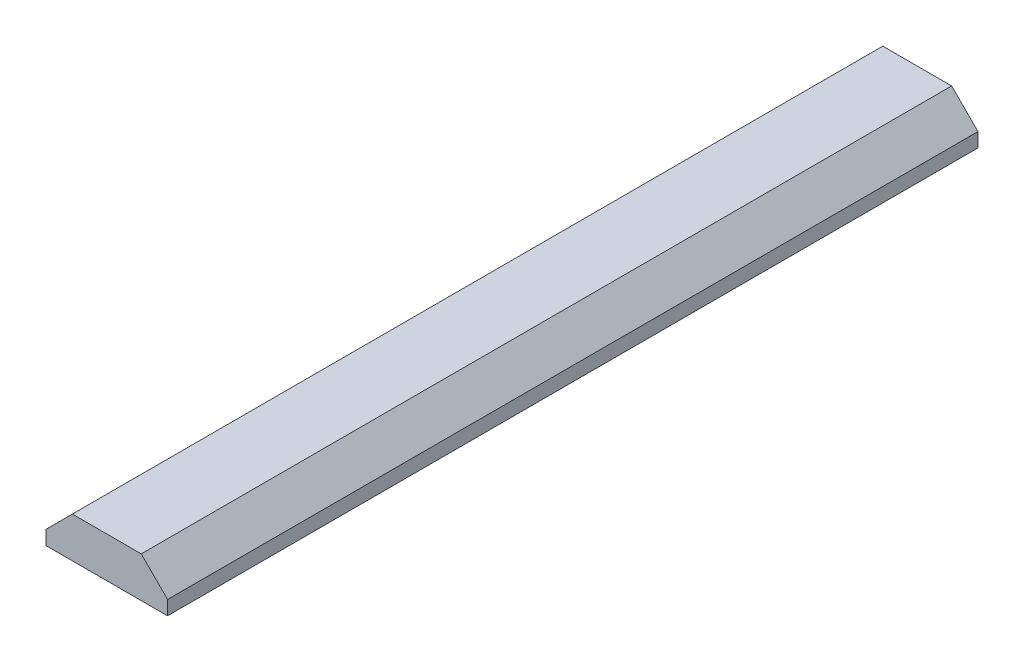
SolidWorks part; units mm, degrees
ref_plane "Ebene vorne" through (0, 0, 0) normal (0, 0, 1) x (1, 0, 0)
ref_plane "Ebene oben" through (0, 0, 0) normal (0, 1, 0) x (1, 0, 0)
ref_plane "Ebene rechts" through (0, 0, 0) normal (1, 0, 0) x (0, 0, -1)
sketch "Skizze1" plane through (0, 0, 0) normal (0, 0, 1) x (1, 0, 0)
  line L0 (0, 0) -> (0, 23680.6173) construction
  line L1 (3.4, 1.8089) -> (-3.4, 1.8089)
  line L2 (-3.4, 1.8089) -> (-6, -0.7911)
  line L3 (-6, -0.7911) -> (-6, -2.1911)
  line L4 (-6, -2.1911) -> (6, -2.1911)
  line L5 (6, -0.7911) -> (6, -2.1911)
  line L6 (3.4, 1.8089) -> (6, -0.7911)
  point P9 (0, -2.1911)
  point P11 (0, 1.8089)
  dimension "D1" = 3.4
  dimension "D2" = 6
  dimension "D3" = 4
  dimension "D4" = 135
extrude "Aufsatz-Linear austragen1" add sketch "Skizze1" along normal blind 80 contours L1 L2 L3 L4 L5 L6
